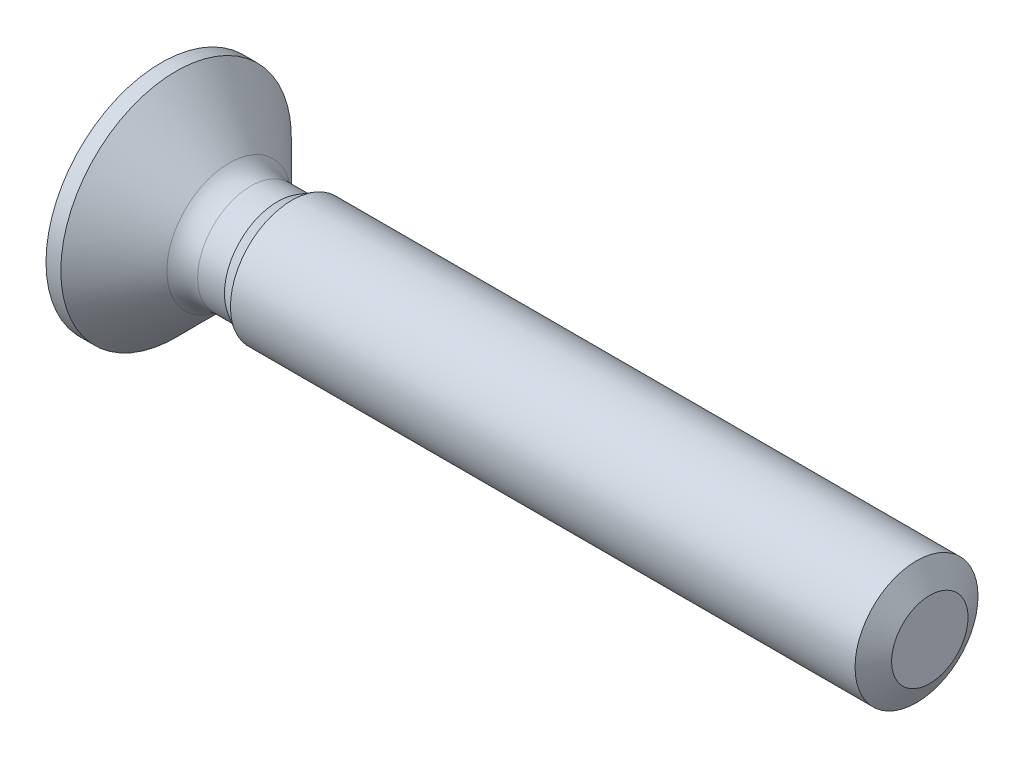
SolidWorks part; units mm, degrees
revolve "基体-旋转" add sketch "草图1" angle 360 about L0
sketch "草图1" plane through (0, 0, 0) normal (0, 0, 1) x (1, 0, 0)
  line L0 (0, 0) -> (4.4175, 0) construction
  line L1 (0, 0) -> (0, 1.5)
  line L2 (0, 1.5) -> (0.1928, 1.5)
  line L3 (0.1928, 1.5) -> (0.8828, 0.81)
  line L4 (1.1657, 0.6928) -> (1.5143, 0.6928)
  line L5 (1.5143, 0.6928) -> (1.7, 0.8)
  line L6 (1.7, 0.8) -> (10, 0.8)
  line L7 (10, 0.8) -> (10, 0)
  line L8 (0, 0) -> (10, 0)
  arc A0 (1.1657, 0.6928) -> (0.8828, 0.81) centre (1.1657, 1.0928) cw
  point P12 (1, 0.6928)
  dimension "D2" = 0.4
  dimension "D1" = 1.3856
  dimension "d" = 1.6
  dimension "dk" = 3
  dimension "k" = 1
  dimension "D5" = 45
  dimension "a" = 0.7
  dimension "l" = 10
  dimension "D8" = 30
cosmetic thread "装饰螺纹线2" parameters "D1"=8.3, "D2"=1.25
material "AISI 304"
ref_plane "前视" through (0, 0, 0) normal (0, 0, 1) x (1, 0, 0)
ref_plane "上视" through (0, 0, 0) normal (0, 1, 0) x (1, 0, 0)
ref_plane "右视" through (0, 0, 0) normal (1, 0, 0) x (0, 0, -1)
sketch "尺寸草图" plane through (0, 0, 0) normal (0, 0, 1) x (1, 0, 0)
  line L0 (0, 0) -> (10, 0)
  point P3 (1, 0)
  point P4 (0.7, 0)
  point P5 (1.6, 0)
  point P6 (3, 0)
  point P7 (8.4, 0)
  point P8 (3.5943, 0)
  point P9 (9.6, 0)
  point P10 (9.1, 0)
  point P11 (9.65, 0)
  dimension "d" = 1.6
  dimension "dk" = 3
  dimension "k" = 1
  dimension "a" = 0.7
  dimension "l" = 10
  dimension "r" = 0.4
  dimension "m" = 1.6
  dimension "h" = 0.9
  dimension "p" = 0.35
sketch "草图2" plane through (0, 0, 0) normal (0, 0, 1) x (1, 0, 0)
  line L0 (9.8269, 0.8) -> (10.1769, 0.8)
  line L1 (10.1769, 0.8) -> (10, 0.4969)
  line L2 (10, 0.4969) -> (9.8269, 0.8)
  line L3 (10, -0.8) -> (10, 0.8) construction
  line L6 (0, 0) -> (-0.4315, 0) construction
  dimension "D1" = 0.35
  dimension "D2" = 0.3031
  dimension "D3" = 0.8
  dimension "D4" = 60
revolve "切除-旋转1" cut sketch "草图2" angle 360 about L6
pattern_linear "阵列(线性)1" [suppressed] count 24 spacing 0.35 along (1, 0, 0)
sketch "草图3" plane through (0, 0, 0) normal (-1, 0, 0) x (0, 0, 1)
  line L0 (0, 0) -> (1.6329, 0) construction
  line L1 (0, 0) -> (0, 0.8499) construction
  line L2 (-0.8, 0.175) -> (0.8, 0.175)
  line L3 (-0.8, 0.175) -> (-0.8, -0.175)
  line L4 (-0.8, -0.175) -> (0.8, -0.175)
  line L5 (0.8, 0.175) -> (0.8, -0.175)
  dimension "m" = 1.6
  dimension "D1" = 0.35
ref_plane "基准面1" through (0.9, 0, 0) normal (-1, 0, 0) x (0, 0, 1)
sketch "草图4" plane through (0.9, 0, 0) normal (-1, 0, 0) x (0, 0, 1)
  point P0 (0, 0)
loft "切除-放样1" cut profiles "草图3", "草图4"
pattern_circular "阵列(圆周)1" count 2 every 90 about axis through (0, 0, 0) along (1, 0, 0) of "切除-放样1"
equation "\"l@草图1\" = \"l@尺寸草图\""
equation "\"k@草图1\" = \"k@尺寸草图\""
equation "\"a@草图1\" = \"a@尺寸草图\""
equation "\"d@草图1\" = \"d@尺寸草图\""
equation "\"dk@草图1\" = \"dk@尺寸草图\""
equation "\"D2@草图1\" = \"r@尺寸草图\""
equation "\"m@草图3\" = \"m@尺寸草图\""
equation "\"h@基准面1\" = \"h@尺寸草图\""
equation "\"D3@阵列(线性)1\" = \"p@尺寸草图\""
equation "\"D3@草图2\" = \"d@草图1\" / 2"
equation "\"D1@装饰螺纹线2\" = \"l@草图1\" - \"k@草图1\" - \"a@草图1\""
equation "\"D2@装饰螺纹线2\" = \"d@尺寸草图\"- \"p@尺寸草图\""
equation "\"D1@阵列(线性)1\" = (  \"l@草图1\" - \"k@草图1\" - \"a@草图1\" )  / \"p@尺寸草图\""
equation "\"D1@草图3\" = \"p@尺寸草图\""
equation "\"D1@草图1\" = \"d@尺寸草图\"*0.866"
equation "\"D2@草图2\" = \"p@尺寸草图\"*0.866"
equation "\"D1@草图2\" = \"p@尺寸草图\""
